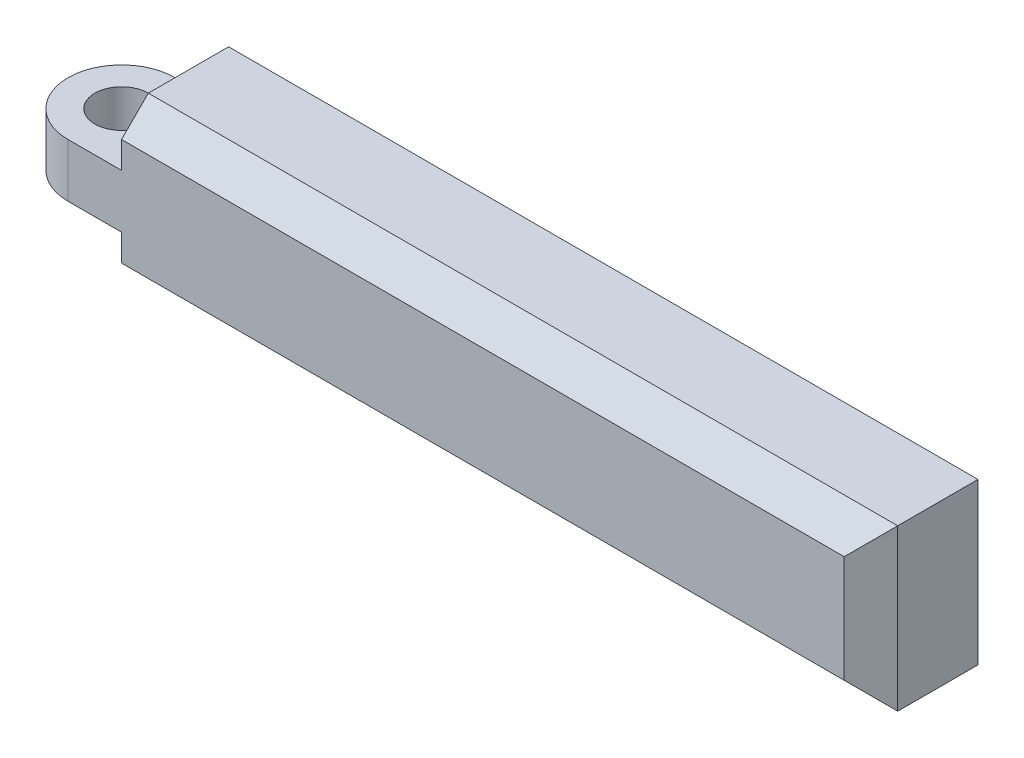
SolidWorks part; units mm, degrees
ref_plane "Front Plane" through (0, 0, 0) normal (0, 0, 1) x (1, 0, 0)
ref_plane "Top Plane" through (0, 0, 0) normal (0, 1, 0) x (1, 0, 0)
ref_plane "Right Plane" through (0, 0, 0) normal (1, 0, 0) x (0, 0, -1)
sketch "Sketch1" plane through (0, 0, 0) normal (0, 1, 0) x (1, 0, 0)
  line L1 (-7, 1) -> (7, 1)
  line L2 (-7, 1) -> (-7, -1)
  line L3 (-7, -1) -> (7, -1)
  line L4 (7, 1) -> (7, -1)
  line L5 (-7, 1) -> (7, -1) construction
  line L6 (-7, -1) -> (7, 1) construction
  point P0 (0, 0)
  dimension "D1" = 14
  dimension "D2" = 2
extrude "Boss-Extrude1" add sketch "Sketch1" along normal blind 3
chamfer "Chamfer1" distance 0.5 angle 45 3 edges at (0, 0, -1) (7, 1.5, -1) (0, 3, -1)
sketch "Sketch2" plane through (-7, 0, 0) normal (-1, 0, 0) x (0, 0, 1)
  line L0 (1, 3) -> (1, 0) construction
  line L1 (-1, 1) -> (1, 1)
  line L2 (-1, 1) -> (-1, 2)
  line L3 (-1, 2) -> (1, 2)
  line L4 (1, 1) -> (1, 2)
  line L5 (-1, 1) -> (1, 2) construction
  line L6 (-1, 2) -> (1, 1) construction
  point P0 (0, 1.5)
  point P8 (1, 1.5)
  dimension "D1" = 1
extrude "Boss-Extrude2" add sketch "Sketch2" along normal blind 2
sketch "Sketch3" plane through (0, 2, 0) normal (0, 1, 0) x (1, 0, 0)
  line L0 (-9, -1) -> (-7, -1) construction
  line L1 (-9, -1) -> (-9, 1) construction
  line L6 (-7, -1) -> (-7, 1)
  line L7 (-7, 1) -> (-9, 1)
  line L8 (-9, 1) -> (-9, -1)
  line L9 (-9, -1) -> (-7, -1)
  line L10 (-7, -1) -> (-7, 1)
  line L11 (-7, 1) -> (-9, 1)
  line L12 (-9, 1) -> (-9, -1)
  line L13 (-9, -1) -> (-7, -1)
  circle A0 centre (-8, 0) radius 1
  circle A1 centre (-8, 0) radius 0.5
  point P4 (-8, -1)
  point P7 (-9, 0)
  line M7 (-9, 1) -> (-9, -1)
  line M8 (-9, -1) -> (-7, -1)
  dimension "D1" = 2
  dimension "D2" = 0.5
  dimension "D3" = 0
extrude "Cut-Extrude1" cut sketch "Sketch3" against normal blind 2 contours A1 | A0 L11 M7 | A0 L12 M8
mirror "Mirror1" about plane through (-7, 3, -1) normal (0, 0, 1) of bodies 103
delete or keep bodies "Body-Delete/Keep 1" type delete bodies bodies 103
